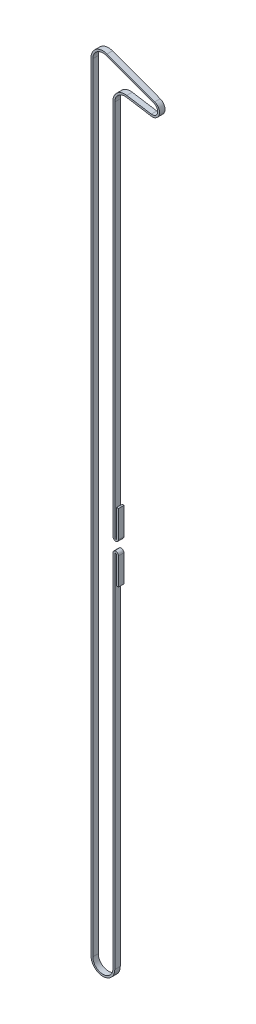
SolidWorks part; units mm, degrees
ref_plane "Front Plane" through (0, 0, 0) normal (0, 0, 1) x (1, 0, 0)
ref_plane "Top Plane" through (0, 0, 0) normal (0, 1, 0) x (1, 0, 0)
ref_plane "Right Plane" through (0, 0, 0) normal (1, 0, 0) x (0, 0, -1)
sketch "Sketch1" plane through (0, 0, 0) normal (0, 0, 1) x (1, 0, 0)
  line L0 (0, 0) -> (0, 100)
  line L1 (0, 100) -> (2, 100) construction
  line L2 (2, 100) -> (2, 0)
  line L3 (2, 0) -> (0, 0) construction
  line L4 (2, 100) -> (2, 116.0994)
  line L5 (16.8065, 126.4197) -> (68.976, 107.1778)
  line L6 (65.95, 95.6241) -> (39.0579, 99.9354)
  line L7 (24, 87.0994) -> (24, -325.1411)
  line L8 (0, 100) -> (0, 116.0994)
  line L9 (17.4986, 128.2962) -> (69.6681, 109.0542)
  line L10 (65.6334, 93.6493) -> (38.7413, 97.9607)
  line L11 (26, 87.0994) -> (26, -325.1411)
  line L12 (2, 0) -> (2, -733.9667)
  line L13 (0, 0) -> (0, -733.9667)
  line L14 (28, -325.1411) -> (28, -295.6287)
  line L16 (28, -340.4889) -> (28, -370.0013)
  line L17 (28, -370.0013) -> (30, -370.0013)
  line L18 (30, -370.0013) -> (30, -340.4889)
  line L21 (28, -295.6287) -> (30, -295.6287)
  line L22 (30, -295.6287) -> (30, -325.1411)
  line L23 (26, -340.4889) -> (26, -733.9667)
  line L25 (24, -340.4889) -> (24, -733.9667)
  arc A1 (2, 116.0994) -> (16.8065, 126.4197) centre (13, 116.0994) cw
  arc A2 (65.95, 95.6241) -> (68.976, 107.1778) centre (66.8998, 101.5485) ccw
  arc A3 (39.0579, 99.9354) -> (24, 87.0994) centre (37, 87.0994) ccw
  arc A4 (0, 116.0994) -> (17.4986, 128.2962) centre (13, 116.0994) cw
  arc A5 (65.6334, 93.6493) -> (69.6681, 109.0542) centre (66.8998, 101.5485) ccw
  arc A6 (38.7413, 97.9607) -> (26, 87.0994) centre (37, 87.0994) ccw
  arc A7 (2, -733.9667) -> (24, -733.9667) centre (13, -733.9667) ccw
  arc A8 (0, -733.9667) -> (26, -733.9667) centre (13, -733.9667) ccw
  arc A11 (24, -340.4889) -> (30, -340.4889) centre (27, -340.4889) cw
  arc A12 (26, -340.4889) -> (28, -340.4889) centre (27, -340.4889) cw
  arc A13 (26, -325.1411) -> (28, -325.1411) centre (27, -325.1411) ccw
  arc A14 (24, -325.1411) -> (30, -325.1411) centre (27, -325.1411) ccw
extrude "Boss-Extrude1" add sketch "Sketch1" along normal blind 6
